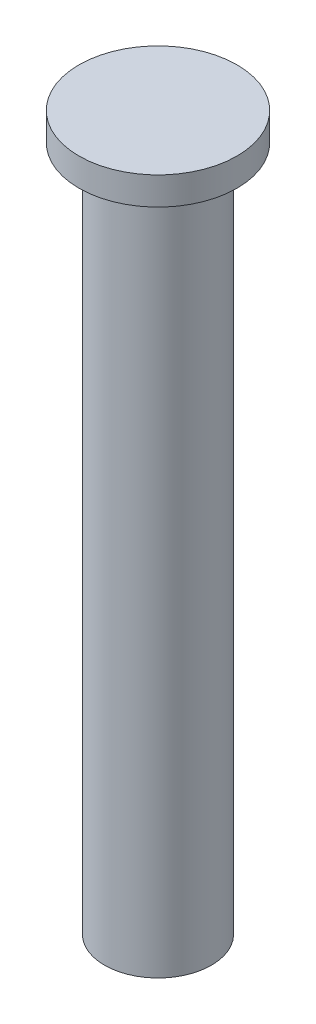
SolidWorks part; units mm, degrees
ref_plane "Front Plane" through (0, 0, 0) normal (0, 0, 1) x (1, 0, 0)
ref_plane "Top Plane" through (0, 0, 0) normal (0, 1, 0) x (1, 0, 0)
ref_plane "Right Plane" through (0, 0, 0) normal (1, 0, 0) x (0, 0, -1)
sketch "Sketch1" plane through (0, 0, 0) normal (0, 1, 0) x (1, 0, 0)
  circle A0 centre (0, 0) radius 2.3
  circle A1 centre (0, 0) radius 1.8
  dimension "D1" = 4.6
extrude "Boss-Extrude1" add sketch "Sketch1" along normal blind 29.5
sketch "Sketch2" plane through (0, 29.5, 0) normal (0, 1, 0) x (1, 0, 0)
  circle A0 centre (0, 0) radius 3.4
extrude "Boss-Extrude2" add sketch "Sketch2" along normal blind 1.2
